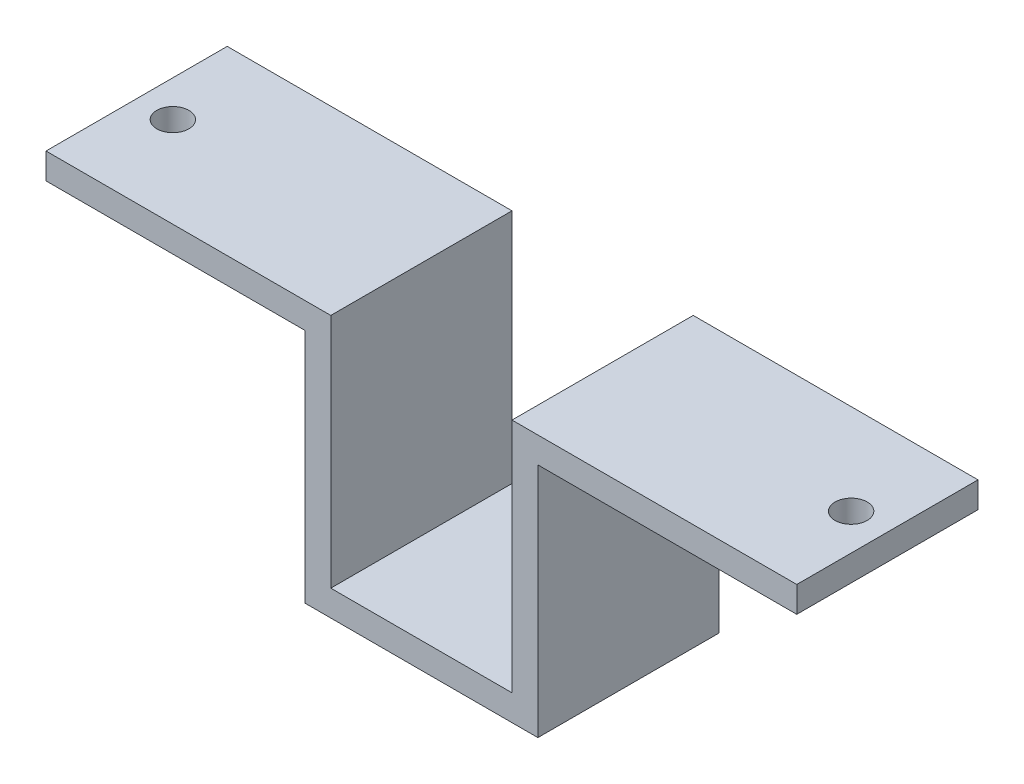
SolidWorks part; units mm, degrees
ref_plane "Front Plane" through (0, 0, 0) normal (0, 0, 1) x (1, 0, 0)
ref_plane "Top Plane" through (0, 0, 0) normal (0, 1, 0) x (1, 0, 0)
ref_plane "Right Plane" through (0, 0, 0) normal (1, 0, 0) x (0, 0, -1)
sketch "Sketch1" plane through (0, 0, 0) normal (0, 0, 1) x (1, 0, 0)
  line L0 (-22.225, 0) -> (22.225, 0)
  line L1 (22.225, 0) -> (22.225, 57.9374)
  line L2 (22.225, 57.9374) -> (28.575, 57.9374)
  line L3 (28.575, 51.5874) -> (28.575, -6.35)
  line L4 (28.575, -6.35) -> (-28.575, -6.35)
  line L5 (-28.575, -6.35) -> (-28.575, 51.5874)
  line L6 (-22.225, 0) -> (-22.225, 57.9374)
  line L7 (-22.225, 57.9374) -> (-28.575, 57.9374)
  line L8 (-28.575, 57.9374) -> (-92.075, 57.9374)
  line L9 (-92.075, 57.9374) -> (-92.075, 51.5874)
  line L10 (-92.075, 51.5874) -> (-28.575, 51.5874)
  line L11 (28.575, 57.9374) -> (92.075, 57.9374)
  line L12 (92.075, 57.9374) -> (92.075, 51.5874)
  line L13 (92.075, 51.5874) -> (28.575, 51.5874)
  line L14 (-28.575, 51.5874) -> (-28.575, 57.9374) construction
  line L15 (28.575, 57.9374) -> (28.575, 51.5874) construction
  line L16 (-22.225, 0) -> (-28.575, 0) construction
  line L17 (22.225, 0) -> (28.575, 0) construction
  point P4 (0, 0)
  dimension "D1" = 44.45
  dimension "D2" = 57.9374
  dimension "D3" = 6.35
  dimension "D4" = 6.35
  dimension "D5" = 6.35
  dimension "D6" = 63.5
extrude "Boss-Extrude1" add sketch "Sketch1" along normal blind 44.45 contours L6 L7 L8 L9 L10 L5 L4 L3 L13 L12 L11 L2 L1 L0
sketch "Sketch2" plane through (0, 51.5874, 0) normal (0, -1, 0) x (1, 0, 0)
  line L0 (28.575, 22.225) -> (92.075, 22.225) construction
  line L1 (28.575, 44.45) -> (28.575, 0) construction
  line L2 (92.075, 44.45) -> (92.075, 0) construction
  line L3 (83.185, 0) -> (83.185, 44.45) construction
  line L4 (92.075, 44.45) -> (28.575, 44.45) construction
  line L5 (0, 44.45) -> (0, 0) construction
  line L6 (28.575, 44.45) -> (-28.575, 44.45) construction
  line L7 (28.575, 0) -> (-28.575, 0) construction
  circle A0 centre (83.185, 22.225) radius 3.937
  circle A1 centre (-83.185, 22.225) radius 3.937
  point P11 (83.185, 22.225)
  dimension "D2" = 7.874
  dimension "D1" = 8.89
extrude "Cut-Extrude1" cut sketch "Sketch2" against normal through all
